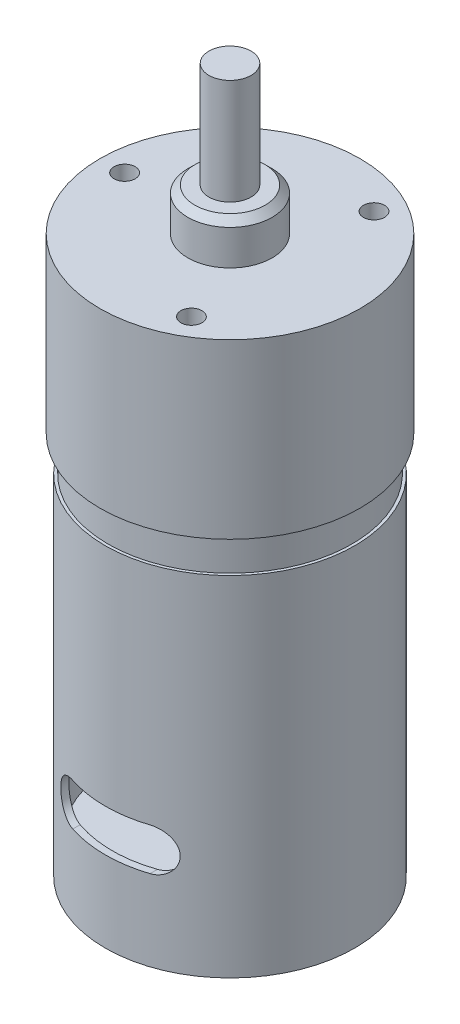
SolidWorks part; units mm, degrees
ref_plane "Plan de face" through (0, 0, 0) normal (0, 0, 1) x (1, 0, 0)
ref_plane "Plan de dessus" through (0, 0, 0) normal (0, 1, 0) x (1, 0, 0)
ref_plane "Plan de droite" through (0, 0, 0) normal (1, 0, 0) x (0, 0, -1)
sketch "Esquisse1" plane through (0, 0, 0) normal (0, 0, 1) x (1, 0, 0)
  line L0 (0, 0) -> (17.75, 0)
  line L1 (18.5, 79.1964) -> (18.5, 54.5964)
  line L2 (18.5, 79.1964) -> (6, 79.1964)
  line L3 (6, 79.1964) -> (6, 85.1964)
  line L4 (6, 85.1964) -> (3, 85.1964)
  line L5 (3, 85.1964) -> (3, 100.1964)
  line L6 (3, 100.1964) -> (0, 100.1964)
  line L7 (0, 100.1964) -> (0, 0)
  line L8 (18.5, 54.5964) -> (17.35, 54.6)
  line L9 (17.35, 54.6) -> (17.35, 49.6)
  line L10 (17.35, 49.6) -> (17.75, 49.6)
  line L11 (17.75, 49.6) -> (17.75, 0)
  dimension "D1" = 3
  dimension "D2" = 6
  dimension "D3" = 18.5
  dimension "D4" = 79.2
  dimension "D5" = 6
  dimension "D6" = 15
  dimension "D7" = 17.35
  dimension "D8" = 5
  dimension "D9" = 24.6
  dimension "D10" = 17.75
  dimension "D11" = 49.6
revolve "Révolution1" add sketch "Esquisse1" angle 360 about L7
fillet "Congé1" [suppressed] radius 1
sketch "Esquisse2" plane through (0, 0, 0) normal (0, 0, 1) x (1, 0, 0)
  line L0 (-5.5, 17.5) -> (5.5, 17.5)
  line L1 (-5.5, 11.5) -> (5.5, 11.5)
  line L2 (0, 0) -> (0, 79.1964) construction
  line L3 (18.5, 79.1964) -> (-18.5, 79.1964) construction
  line L4 (-17.75, 0) -> (17.75, 0) construction
  arc A0 (-5.5, 17.5) -> (-5.5, 11.5) centre (-5.5, 14.5) ccw
  arc A1 (5.5, 17.5) -> (5.5, 11.5) centre (5.5, 14.5) cw
  point P9 (0, 11.5)
  point P10 (0, 17.5)
  dimension "D1" = 6
  dimension "D2" = 11
  dimension "D3" = 11.5
extrude "Extrusion1" cut sketch "Esquisse2" along normal up to next and the other way up to next
chamfer "Chanfrein1" distance 1 angle 45 1 edges at (0, 85.1964, 6)
sketch "Esquisse3" plane through (0, 0, 0) normal (0, -1, 0) x (1, 0, 0)
  circle A0 centre (0, 0) radius 16.75
  dimension "D1" = 33.5
extrude "Extrusion2" cut sketch "Esquisse3" against normal blind 49
sketch "Esquisse6" plane through (0, 0, 0) normal (0, -1, 0) x (1, 0, 0)
  circle A0 centre (0, 0) radius 17.75
  dimension "D1" = 35.5
extrude "Extrusion3" add sketch "Esquisse6" against normal blind 5
sketch "Esquisse8" plane through (0, 79.1964, 0) normal (0, 1, 0) x (-1, 0, 0)
  line L0 (0, 0) -> (18.5, 0) construction
  line L1 (0, 0) -> (-9.25, -16.0215) construction
  line L2 (0, 0) -> (-9.25, 16.0215) construction
  circle A0 centre (0, 0) radius 18.5 construction
  circle A1 centre (15, 0) radius 1.5
  circle A2 centre (-7.5, -12.9904) radius 1.5
  circle A3 centre (-7.5, 12.9904) radius 1.5
  point P5 (15, 0)
  point P10 (-7.5, -12.9904)
  point P11 (-7.5, 12.9904)
  dimension "D3" = 3
  dimension "D1" = 120
  dimension "D2" = 120
  dimension "D4" = 15
  dimension "D5" = 15
  dimension "D6" = 15
extrude "Extrusion4" cut sketch "Esquisse8" against normal blind 5
